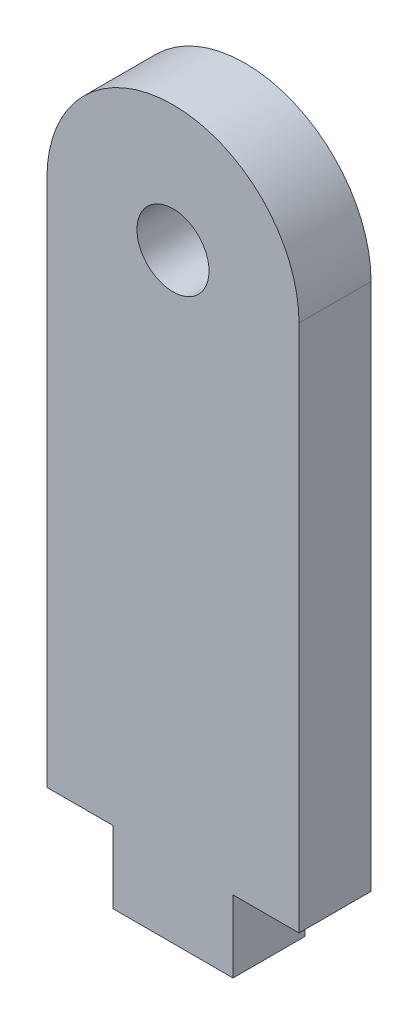
SolidWorks part; units mm, degrees
ref_plane "Front Plane" through (0, 0, 0) normal (0, 0, 1) x (1, 0, 0)
ref_plane "Top Plane" through (0, 0, 0) normal (0, 1, 0) x (1, 0, 0)
ref_plane "Right Plane" through (0, 0, 0) normal (1, 0, 0) x (0, 0, -1)
sketch "Sketch1" plane through (0, 0, 0) normal (0, 0, 1) x (1, 0, 0)
  line L0 (10.5, 25) -> (10.5, 3)
  line L1 (10.5, 3) -> (7.75, 3)
  line L2 (7.75, 3) -> (7.75, 0)
  line L3 (7.75, 0) -> (2.75, 0)
  line L4 (2.75, 0) -> (2.75, 3)
  line L5 (2.75, 3) -> (0, 3)
  line L6 (0, 3) -> (0, 25)
  arc A0 (5.25, 26.5) -> (5.25, 23.5) centre (5.25, 25) ccw
  arc A1 (5.25, 23.5) -> (5.25, 26.5) centre (5.25, 25) ccw
  arc A2 (0, 25) -> (5.25, 30.25) centre (5.25, 25) cw
  arc A3 (5.25, 30.25) -> (10.5, 25) centre (5.25, 25) cw
extrude "Plate_thickness_3mm" add sketch "Sketch1" along normal blind 3
